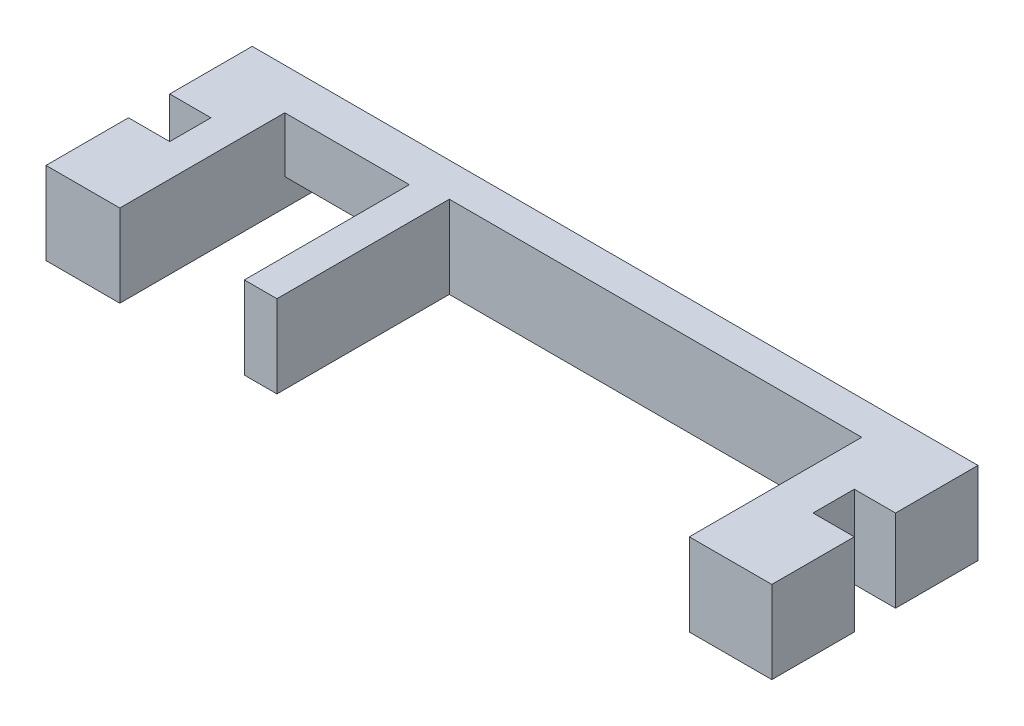
SolidWorks part; units mm, degrees
ref_plane "Front Plane" through (0, 0, 0) normal (0, 0, 1) x (1, 0, 0)
ref_plane "Top Plane" through (0, 0, 0) normal (0, 1, 0) x (1, 0, 0)
ref_plane "Right Plane" through (0, 0, 0) normal (1, 0, 0) x (0, 0, -1)
sketch "Sketch1" plane through (0, 0, 0) normal (0, 1, 0) x (1, 0, 0)
  line L1 (-49, 12.5) -> (49, 12.5)
  line L2 (-49, 12.5) -> (-49, -12.5)
  line L3 (-49, -12.5) -> (49, -12.5)
  line L4 (49, 12.5) -> (49, -12.5)
  line L5 (-49, 12.5) -> (49, -12.5) construction
  line L6 (-49, -12.5) -> (49, 12.5) construction
  point P0 (0, 0)
extrude "Boss-Extrude1" add sketch "Sketch1" along normal blind 10
sketch "Sketch4" plane through (-49, 0, 0) normal (-1, 0, 0) x (0, 0, 1)
  line L1 (-12.5, 0) -> (12.5, 0)
  line L2 (-12.5, 0) -> (-12.5, 10)
  line L3 (-12.5, 10) -> (12.5, 10)
  line L4 (12.5, 0) -> (12.5, 10)
extrude "Cut-Extrude6" cut sketch "Sketch4" against normal blind 5
sketch "Sketch5" plane through (49, 0, 0) normal (1, 0, 0) x (0, 0, -1)
  line L1 (12.5, 10) -> (-12.5, 10)
  line L2 (12.5, 10) -> (12.5, 0)
  line L3 (12.5, 0) -> (-12.5, 0)
  line L4 (-12.5, 10) -> (-12.5, 0)
extrude "Cut-Extrude7" cut sketch "Sketch5" against normal blind 5
sketch "Sketch6" plane through (44, 0, 0) normal (1, 0, 0) x (0, 0, -1)
  line L1 (12.5, 10) -> (-12.5, 10) construction
  line L2 (-2.5, 10) -> (2.5, 10)
  line L3 (2.5, 10) -> (2.5, 0)
  line L4 (-12.5, 0) -> (12.5, 0) construction
  line L5 (2.5, 0) -> (-2.5, 0)
  line L6 (-2.5, 10) -> (-2.5, 0)
extrude "Cut-Extrude8" cut sketch "Sketch6" against normal blind 5
sketch "Sketch7" plane through (-44, 0, 0) normal (-1, 0, 0) x (0, 0, 1)
  line L1 (-2.5, 0) -> (2.5, 0)
  line L2 (-2.5, 0) -> (-2.5, 10)
  line L3 (-2.5, 10) -> (2.5, 10)
  line L4 (2.5, 0) -> (2.5, 10)
extrude "Cut-Extrude9" cut sketch "Sketch7" against normal blind 5
sketch "Sketch8" plane through (0, 10, 0) normal (0, 1, 0) x (1, 0, 0)
  line L0 (-16, -12.5) -> (-16, 8.4)
  line L1 (-16, 8.4) -> (34, 8.4)
  line L2 (34, 8.4) -> (34, -12.5)
  line L3 (-44, -12.5) -> (44, -12.5) construction
  line L4 (34, 8.4) -> (34, -12.5) construction
  line L5 (34, -12.5) -> (-16, -12.5)
extrude "Cut-Extrude10" cut sketch "Sketch8" against normal blind 13
sketch "Sketch9" plane through (0, 10, 0) normal (0, 1, 0) x (1, 0, 0)
  line L0 (-35.05, -12.5) -> (-35.05, 7.5)
  line L1 (-35.05, 7.5) -> (-19.95, 7.5)
  line L2 (-19.95, 7.5) -> (-19.95, -12.5)
  line L11 (-39, 0) -> (-16, 0)
  line L12 (-39, -2.5) -> (-39, 2.5) construction
  line L13 (-16, 8.4) -> (-16, -12.5) construction
  line L14 (-44, -12.5) -> (-16, -12.5) construction
  line L15 (-35.05, 12.5) -> (-19.95, 12.5) construction
  line L16 (-35.05, 12.5) -> (-35.05, -12.5) construction
  line L17 (-35.05, -12.5) -> (-19.95, -12.5) construction
  line L18 (-19.95, 12.5) -> (-19.95, -12.5) construction
  line L19 (-35.05, -12.5) -> (-19.95, -12.5)
  point P7 (-27.5, 0)
  point P8 (-27.5, 0)
  line M25 (-44, -12.5) -> (-16, -12.5)
extrude "Cut-Extrude11" cut sketch "Sketch9" against normal blind 13 contours L0 L11 L2 L1 | L11 L0 L2 M25
sketch "Sketch10" plane through (0, 0, 0) normal (0, -1, 0) x (1, 0, 0)
  line L0 (-19.95, -7.5) -> (-19.95, -12.5)
  line L1 (44, -12.5) -> (-44, -12.5) construction
  line L3 (-35.05, -7.5) -> (-35.05, -12.5)
  line L4 (-35.05, -12.5) -> (-19.95, -12.5)
  line L5 (-19.95, -7.5) -> (-35.05, -7.5)
extrude "Cut-Extrude12" cut sketch "Sketch10" against normal blind 3.3
